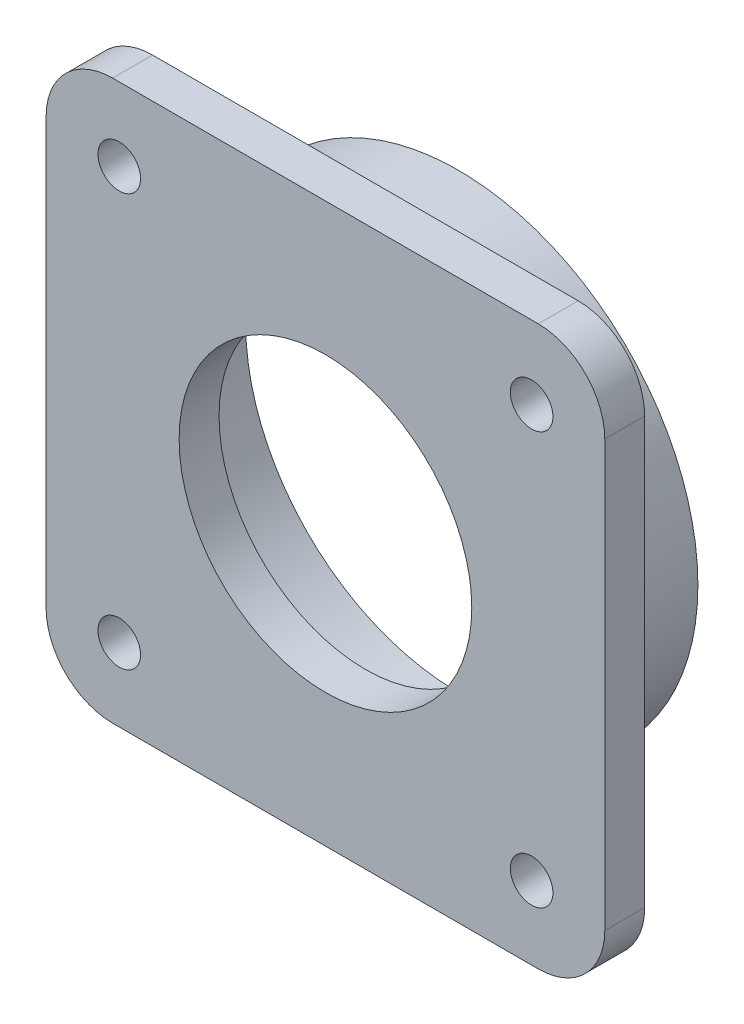
SolidWorks part; units mm, degrees
ref_plane "前视基准面" through (0, 0, 0) normal (0, 0, 1) x (1, 0, 0)
ref_plane "上视基准面" through (0, 0, 0) normal (0, 1, 0) x (1, 0, 0)
ref_plane "右视基准面" through (0, 0, 0) normal (1, 0, 0) x (0, 0, -1)
other "Configuration Table"
sketch "草图1" plane through (0, 0, 0) normal (0, 0, 1) x (1, 0, 0)
  line L1 (-21, -21) -> (21, -21)
  line L2 (-21, -21) -> (-21, 21)
  line L3 (-21, 21) -> (21, 21)
  line L4 (21, -21) -> (21, 21)
  line L5 (-21, -21) -> (21, 21) construction
  line L6 (-21, 21) -> (21, -21) construction
  line L7 (-15.5, -15.5) -> (15.5, -15.5)
  line L8 (-15.5, -15.5) -> (-15.5, 15.5)
  line L9 (-15.5, 15.5) -> (15.5, 15.5)
  line L10 (15.5, -15.5) -> (15.5, 15.5)
  line L11 (-15.5, -15.5) -> (15.5, 15.5) construction
  line L12 (-15.5, 15.5) -> (15.5, -15.5) construction
  circle A0 centre (-15.5, 15.5) radius 1.6
  circle A1 centre (15.5, 15.5) radius 1.6
  circle A2 centre (15.5, -15.5) radius 1.6
  circle A3 centre (-15.5, -15.5) radius 1.6
  circle A4 centre (0, 0) radius 11
  point P0 (0, 0)
  point P6 (0, 0)
  point P21 (0, 0)
  dimension "D4" = 3.2
  dimension "D6" = 22
  dimension "D1" = 42
  dimension "D2" = 42
  dimension "D3" = 31
  dimension "D5" = 4
extrude "凸台-拉伸1" add sketch "草图1" along normal blind 3 contours A3 L7 A2 L10 A1 L9 A0 L8 A4 | L1 L4 L3 L2 A3 L8 A0 L9 A1 L10 A2 L7
fillet "圆角1" radius 5 4 edges at (-21, -21, 1.5) (21, -21, 1.5) (21, 21, 1.5) (-21, 21, 1.5)
sketch "草图2" plane through (0, 0, 0) normal (0, 0, -1) x (-1, 0, 0)
  circle A0 centre (0, 0) radius 16
  circle A1 centre (0, 0) radius 18
  dimension "D1" = 32
  dimension "D2" = 2
extrude "凸台-拉伸2" add sketch "草图2" along normal blind 7
